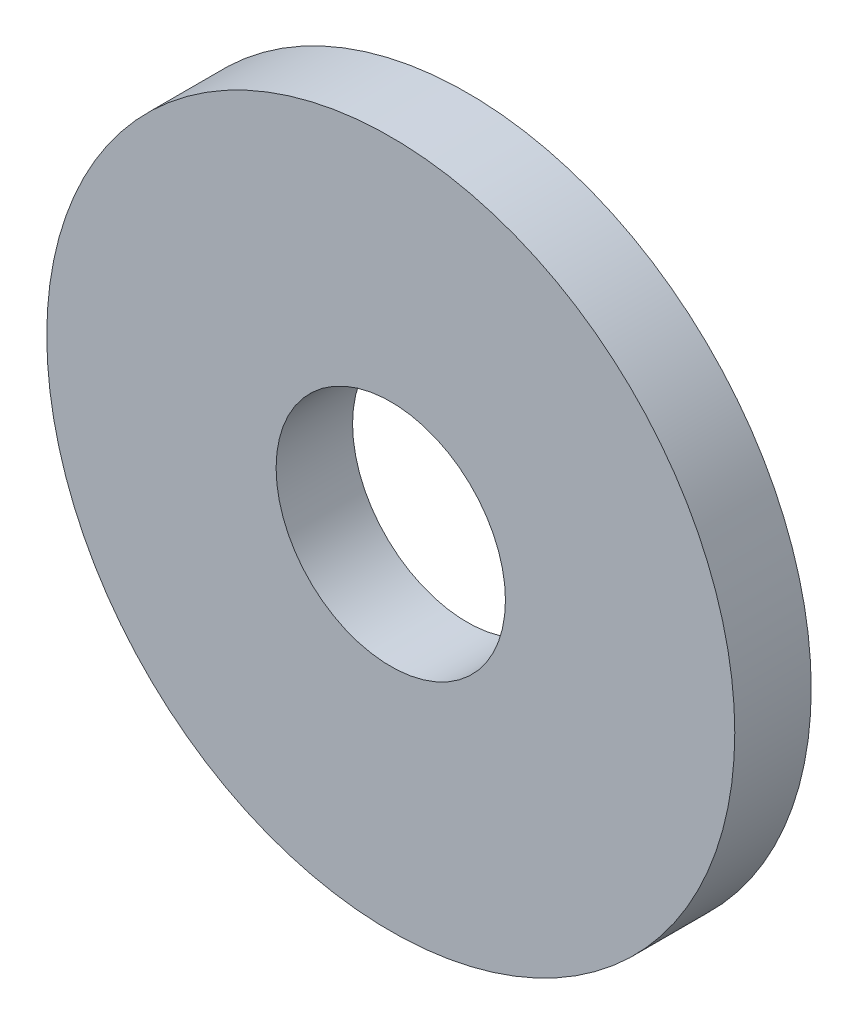
SolidWorks part; units mm, degrees
material "合金钢 (SS)"
ref_plane "前视基准面" through (0, 0, 0) normal (0, 0, 1) x (1, 0, 0)
ref_plane "上视基准面" through (0, 0, 0) normal (0, 1, 0) x (1, 0, 0)
ref_plane "右视基准面" through (0, 0, 0) normal (1, 0, 0) x (0, 0, -1)
sketch "草图1" plane through (0, 0, 0) normal (0, 0, 1) x (1, 0, 0)
  circle A0 centre (0, 0) radius 1.5
  circle A1 centre (0, 0) radius 4.5
  dimension "D1" = 3
  dimension "D2" = 9
extrude "凸台-拉伸1" add sketch "草图1" along normal mid plane 1
